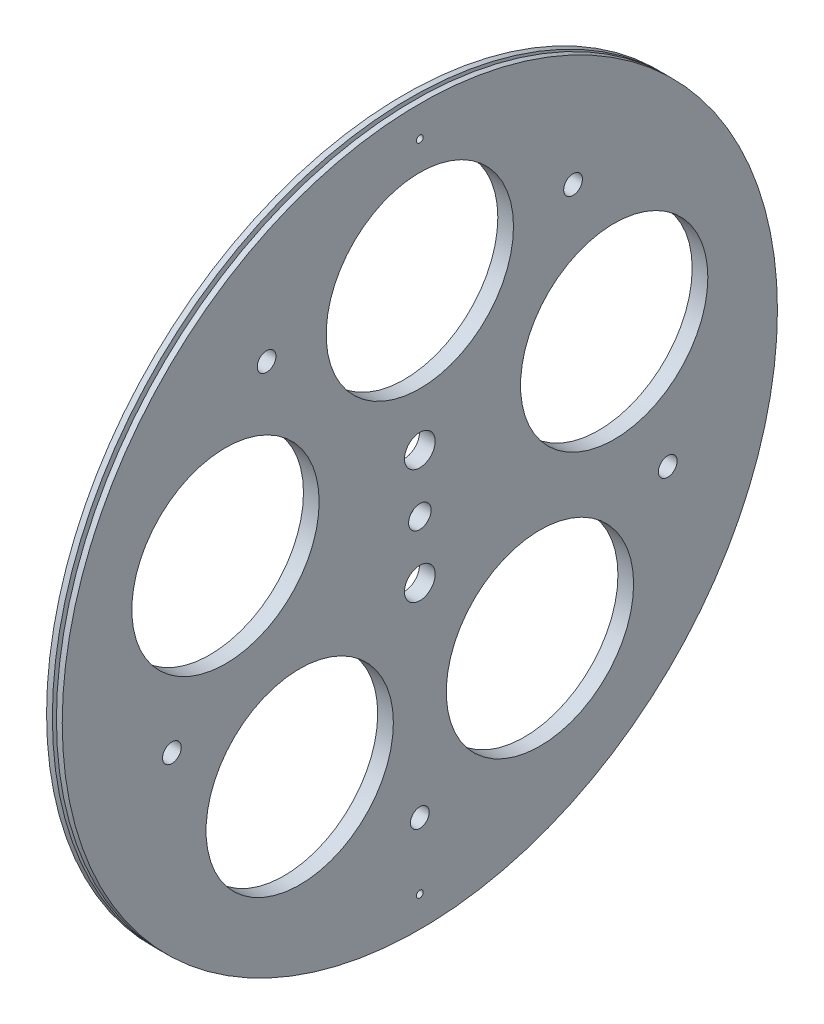
SolidWorks part; units mm, degrees
other "标注1"
sketch "草图21" plane through (3.5, 105, 105) normal (0.1418, 0.3553, 0.9239) x (0.9336, 0.2622, -0.2441)
ref_plane "前视基准面" through (0, 0, 0) normal (0, 0, 1) x (1, 0, 0)
ref_plane "上视基准面" through (0, 0, 0) normal (0, 1, 0) x (1, 0, 0)
ref_plane "右视基准面" through (0, 0, 0) normal (1, 0, 0) x (0, 0, -1)
other "Configuration Table"
sketch "草图1" plane through (0, 0, 0) normal (0, 0, 1) x (1, 0, 0)
  line L0 (0, 0) -> (-10, 0)
  line L4 (-21.9, 25) -> (-21.9, 105)
  line L5 (-21.9, 105) -> (-23, 105)
  line L6 (-26.5, 105) -> (-26.5, 11)
  line L7 (-21, 0) -> (-10, 0)
  line L8 (-26.5, 105) -> (-26.5, 98.3074)
  line L9 (-26.5, 105) -> (-25, 105)
  line L10 (-21.9, 105) -> (-23, 105)
  line L11 (-25, 105) -> (-26.5, 105)
  line L13 (-24.8, 95) -> (-23.6, 95)
  line L14 (-24.2, 95) -> (-24.8, 95)
  line L15 (-23.6, 95) -> (-24.2, 95)
  line L16 (-24.8, 95) -> (-24.8, 105)
  line L17 (-24.8, 105) -> (-25, 105)
  line L18 (-23.6, 95) -> (-23.6, 105)
  line L19 (-23.6, 105) -> (-23, 105)
  line L20 (-21.9, 25) -> (-21.9, 11)
  line L21 (-26.5, 11) -> (-26.5, 0)
  line L22 (-21.9, 11) -> (-21.9, 0)
  line L23 (-21.9, 0) -> (-26.5, 0)
  dimension "D9" = 0.6
  dimension "D2" = 4.6
  dimension "D3" = 1.7
  dimension "D4" = 105
  dimension "D10" = 95
  dimension "D11" = 0.6
revolve "旋转1" add sketch "草图1" angle 360 about L7
ref_plane "基准面2" through (0, 25, 0) normal (0, 1, 0) x (1, 0, 0)
ref_plane "基准面3" through (0, 0, 25) normal (0, 0, 1) x (1, 0, 0)
sketch "草图22" plane through (-21.9, 0, 0) normal (1, 0, 0) x (0, 0, -1)
  line L0 (0, 0) -> (0, 105)
  line L1 (0, 0) -> (0, 60)
  line L2 (0, 105) -> (0, 96)
  line L3 (0, 0) -> (7.0138, 0)
  line L6 (35.2671, -48.541) -> (57.0634, 18.541)
  line L9 (46.1653, -15) -> (72.7948, -23.6525)
  circle A0 centre (0, 0) radius 105 construction
  circle A1 centre (0, 60) radius 27.5
  circle A2 centre (57.0634, 18.541) radius 27.5
  circle A3 centre (35.2671, -48.541) radius 27.5
  circle A4 centre (-35.2671, -48.541) radius 27.5
  circle A5 centre (-57.0634, 18.541) radius 27.5
  circle A6 centre (0, 96) radius 1
  circle A7 centre (0, 0) radius 16.9
  circle A8 centre (0, 16.9) radius 4.5
  circle A11 centre (0, -96) radius 1
  circle A12 centre (0, -16.9) radius 4.5
  circle A13 centre (72.7948, -23.6525) radius 2.75
  circle A14 centre (0, -76.541) radius 2.75
  circle A15 centre (-72.7948, -23.6525) radius 2.75
  circle A16 centre (-44.9897, 61.923) radius 2.75
  circle A17 centre (44.9897, 61.923) radius 2.75
  circle A18 centre (0, 0) radius 3.3
  point P18 (0, 0)
  point P28 (0, 0)
  point P41 (0, 0)
  dimension "D1" = 5
  dimension "D3" = 55
  dimension "D4" = 9
  dimension "D5" = 33.8
  dimension "D6" = 5
  dimension "D7" = 28
  dimension "D8" = 5.5
  dimension "D9" = 6.6
  dimension "D2" = 60
extrude "切除-拉伸1" cut sketch "草图22" against normal blind 10
sketch3d "3D草图1"
  circle A5 centre (-24.2, 0, 0) radius 95
  point P2 (70.8, 0, 0)
  point P4 (26.7871, 0, 0)
  point P5 (-52.9521, 0, 0)
  point P6 (-68.124, 0, 0)
  dimension "D1" = 190
  dimension "D2" = 24.2
